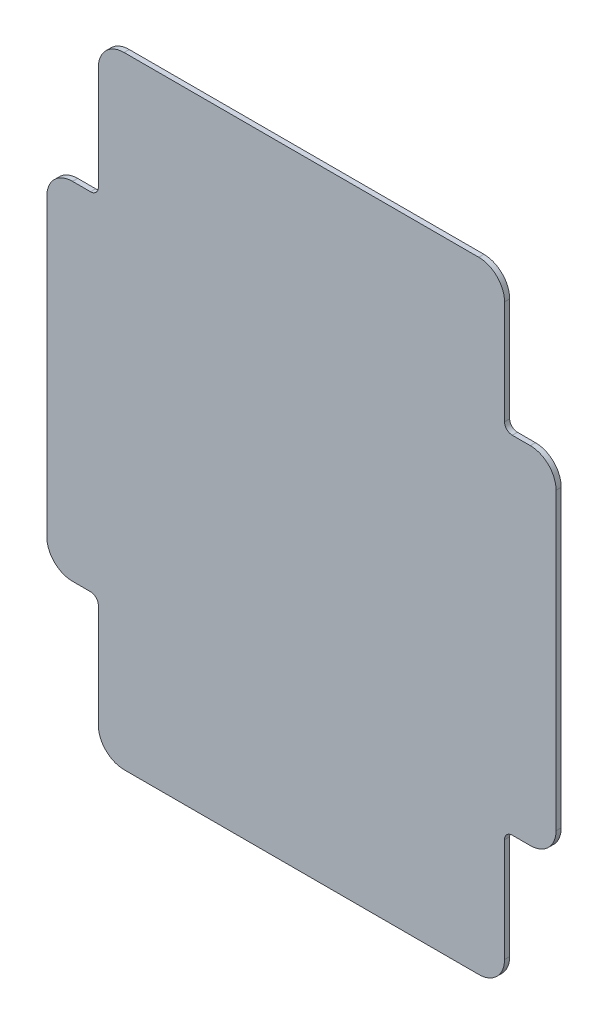
SolidWorks part; units mm, degrees
ref_plane "Ön Düzlem" through (0, 0, 0) normal (0, 0, 1) x (1, 0, 0)
ref_plane "Üst Düzlem" through (0, 0, 0) normal (0, 1, 0) x (1, 0, 0)
ref_plane "Sağ Düzlem" through (0, 0, 0) normal (1, 0, 0) x (0, 0, -1)
sketch "Çizim1" plane through (0, 0, 0) normal (0, 0, 1) x (1, 0, 0)
  line L0 (78.3978, 53) -> (78.3978, 58)
  line L1 (78.3978, 58) -> (-79.2022, 58)
  line L2 (-79.2022, 58) -> (-79.2022, 53)
  line L3 (-79.2022, 53) -> (-79.2022, 4.7)
  line L4 (-79.2022, 4.7) -> (-99.2022, 4.7)
  line L5 (-99.2022, 4.7) -> (-99.2022, -129.7)
  line L6 (-99.2022, -129.7) -> (-79.2022, -129.7)
  line L7 (-79.2022, -129.7) -> (-79.2022, -178)
  line L8 (-79.2022, -178) -> (-79.2022, -183)
  line L9 (-79.2022, -183) -> (78.3978, -183)
  line L10 (78.3978, -183) -> (78.3978, -178)
  line L11 (78.3978, -178) -> (78.3978, -129.7)
  line L12 (78.3978, -129.7) -> (98.3978, -129.7)
  line L13 (98.3978, -129.7) -> (98.3978, 4.7)
  line L14 (98.3978, 4.7) -> (78.3978, 4.7)
  line L15 (78.3978, 4.7) -> (78.3978, 53)
  dimension "D1" = 5
  dimension "D2" = 5
  dimension "D3" = 20
  dimension "D4" = 20
extrude "Yükseklik-Ekstrüzyon1" add sketch "Çizim1" along normal blind 2 contours L3 L4 L5 L6 L7 L8 L9 L10 L11 L12 L13 L14 L15 L0 L1 L2
fillet "Radyus1" radius 10 8 edges at (-79.2022, 58, 1) (-99.2022, 4.7, 1) (-99.2022, -129.7, 1) (-79.2022, -183, 1) (78.3978, -183, 1) (98.3978, -129.7, 1) (98.3978, 4.7, 1) (78.3978, 58, 1)
fillet "Radyus2" radius 3 4 edges at (-79.2022, -129.7, 1) (78.3978, -129.7, 1) (78.3978, 4.7, 1) (-79.2022, 4.7, 1)
sketch "Çizim2" plane through (0, 0, 0) normal (0, 0, -1) x (-1, 0, 0)
  line L0 (69.2022, -183) -> (-68.3978, -183) construction
  line L1 (-59.5978, -145.55) -> (-57.4978, -145.55)
  line L2 (-59.5978, -145.55) -> (-59.5978, -173.55)
  line L3 (-59.5978, -173.55) -> (-57.4978, -173.55)
  line L4 (-57.4978, -145.55) -> (-57.4978, -173.55)
  line L5 (-78.3978, -173) -> (-78.3978, -132.7) construction
  line L6 (0.4022, 58) -> (0.4022, -183) construction
  line L7 (-68.3978, 58) -> (69.2022, 58) construction
  line L8 (-98.3978, -62.5) -> (99.2022, -62.5) construction
  line L9 (-98.3978, -119.7) -> (-98.3978, -5.3) construction
  line L10 (99.2022, -5.3) -> (99.2022, -119.7) construction
  line L11 (58.3022, -145.55) -> (58.3022, -173.55)
  line L12 (60.4022, -173.55) -> (58.3022, -173.55)
  line L13 (60.4022, -145.55) -> (60.4022, -173.55)
  line L14 (60.4022, -145.55) -> (58.3022, -145.55)
  line L15 (60.4022, 20.55) -> (58.3022, 20.55)
  line L16 (60.4022, 20.55) -> (60.4022, 48.55)
  line L17 (60.4022, 48.55) -> (58.3022, 48.55)
  line L18 (58.3022, 20.55) -> (58.3022, 48.55)
  line L19 (-57.4978, 20.55) -> (-57.4978, 48.55)
  line L20 (-59.5978, 48.55) -> (-57.4978, 48.55)
  line L21 (-59.5978, 20.55) -> (-59.5978, 48.55)
  line L22 (-59.5978, 20.55) -> (-57.4978, 20.55)
  dimension "D1" = 2.1
  dimension "D2" = 9.45
  dimension "D3" = 18.8
  dimension "D4" = 28
extrude "Kes-Ekstrüzyon1" [suppressed] cut sketch "Çizim2" against normal blind 10
sketch "Çizim3" plane through (0, 0, 0) normal (0, 0, -1) x (-1, 0, 0)
  line L0 (79.5821, -100.537) -> (63.7567, -100.537)
  line L1 (59.7567, -104.537) -> (59.7567, -105.7328)
  line L2 (55.7567, -109.7328) -> (52.471, -109.7328)
  line L3 (48.471, -105.7328) -> (48.471, -76.5317)
  line L4 (48.471, -65.4259) -> (42.4393, -65.4259)
  line L5 (38.4393, -61.4259) -> (38.4393, -0.4577)
  line L6 (42.4393, 3.5423) -> (50.1138, 3.5423)
  line L7 (54.1138, -0.4577) -> (54.1138, -16.2831)
  line L8 (58.1138, -20.2831) -> (79.5821, -20.2831)
  line L9 (83.5821, -24.2831) -> (83.5821, -61.4259)
  line L10 (0.4022, -183) -> (0.4022, 58) construction
  line L11 (48.471, -65.4259) -> (79.5821, -65.4259)
  line L13 (52.471, -72.5317) -> (79.5821, -72.5317)
  line L15 (69.2022, -183) -> (-68.3978, -183) construction
  line L16 (-68.3978, 58) -> (69.2022, 58) construction
  line L31 (83.5821, -76.5317) -> (83.5821, -96.537)
  line L33 (-82.7776, -76.5317) -> (-82.7776, -96.537)
  line L34 (-51.6665, -72.5317) -> (-78.7776, -72.5317)
  line L35 (-47.6665, -65.4259) -> (-78.7776, -65.4259)
  line L36 (-82.7776, -24.2831) -> (-82.7776, -61.4259)
  line L37 (-57.3094, -20.2831) -> (-78.7776, -20.2831)
  line L38 (-53.3094, -0.4577) -> (-53.3094, -16.2831)
  line L39 (-41.6348, 3.5423) -> (-49.3094, 3.5423)
  line L40 (-37.6348, -61.4259) -> (-37.6348, -0.4577)
  line L41 (-47.6665, -65.4259) -> (-41.6348, -65.4259)
  line L42 (-47.6665, -105.7328) -> (-47.6665, -76.5317)
  line L43 (-54.9522, -109.7328) -> (-51.6665, -109.7328)
  line L44 (-58.9522, -104.537) -> (-58.9522, -105.7328)
  line L45 (-78.7776, -100.537) -> (-62.9522, -100.537)
  arc A0 (79.5821, -65.4259) -> (83.5821, -61.4259) centre (79.5821, -61.4259) ccw
  arc A1 (79.5821, -20.2831) -> (83.5821, -24.2831) centre (79.5821, -24.2831) cw
  arc A2 (54.1138, -16.2831) -> (58.1138, -20.2831) centre (58.1138, -16.2831) ccw
  arc A3 (50.1138, 3.5423) -> (54.1138, -0.4577) centre (50.1138, -0.4577) cw
  arc A4 (38.4393, -0.4577) -> (42.4393, 3.5423) centre (42.4393, -0.4577) cw
  arc A5 (42.4393, -65.4259) -> (38.4393, -61.4259) centre (42.4393, -61.4259) cw
  arc A6 (52.471, -109.7328) -> (48.471, -105.7328) centre (52.471, -105.7328) cw
  arc A7 (48.471, -76.5317) -> (52.471, -72.5317) centre (52.471, -76.5317) cw
  arc A8 (79.5821, -72.5317) -> (83.5821, -76.5317) centre (79.5821, -76.5317) cw
  arc A9 (79.5821, -100.537) -> (83.5821, -96.537) centre (79.5821, -96.537) ccw
  arc A10 (63.7567, -100.537) -> (59.7567, -104.537) centre (63.7567, -104.537) ccw
  arc A11 (59.7567, -105.7328) -> (55.7567, -109.7328) centre (55.7567, -105.7328) cw
  arc A12 (-58.9522, -105.7328) -> (-54.9522, -109.7328) centre (-54.9522, -105.7328) ccw
  arc A13 (-62.9522, -100.537) -> (-58.9522, -104.537) centre (-62.9522, -104.537) cw
  arc A14 (-78.7776, -100.537) -> (-82.7776, -96.537) centre (-78.7776, -96.537) cw
  arc A15 (-78.7776, -72.5317) -> (-82.7776, -76.5317) centre (-78.7776, -76.5317) ccw
  arc A16 (-47.6665, -76.5317) -> (-51.6665, -72.5317) centre (-51.6665, -76.5317) ccw
  arc A17 (-51.6665, -109.7328) -> (-47.6665, -105.7328) centre (-51.6665, -105.7328) ccw
  arc A18 (-41.6348, -65.4259) -> (-37.6348, -61.4259) centre (-41.6348, -61.4259) ccw
  arc A19 (-37.6348, -0.4577) -> (-41.6348, 3.5423) centre (-41.6348, -0.4577) ccw
  arc A20 (-49.3094, 3.5423) -> (-53.3094, -0.4577) centre (-49.3094, -0.4577) ccw
  arc A21 (-53.3094, -16.2831) -> (-57.3094, -20.2831) centre (-57.3094, -16.2831) cw
  arc A22 (-78.7776, -20.2831) -> (-82.7776, -24.2831) centre (-78.7776, -24.2831) ccw
  arc A23 (-78.7776, -65.4259) -> (-82.7776, -61.4259) centre (-78.7776, -61.4259) cw
  point P34 (83.5821, -65.4259)
  point P37 (83.5821, -20.2831)
  point P40 (54.1138, -20.2831)
  point P43 (54.1138, 3.5423)
  point P46 (38.4393, 3.5423)
  point P49 (38.4393, -65.4259)
  point P52 (48.471, -109.7328)
  point P55 (48.471, -72.5317)
  point P58 (83.5821, -72.5317)
  point P61 (83.5821, -100.537)
  point P64 (59.7567, -100.537)
  point P67 (59.7567, -109.7328)
  point P92 (-58.9522, -109.7328)
  point P93 (-58.9522, -100.537)
  point P94 (-82.7776, -100.537)
  point P95 (-82.7776, -72.5317)
  point P96 (-47.6665, -72.5317)
  point P97 (-47.6665, -109.7328)
  point P98 (-37.6348, -65.4259)
  point P99 (-37.6348, 3.5423)
  point P100 (-53.3094, 3.5423)
  point P101 (-53.3094, -20.2831)
  point P102 (-82.7776, -20.2831)
  point P103 (-82.7776, -65.4259)
  dimension "D1" = 4
extrude "Kes-Ekstrüzyon2" [suppressed] cut sketch "Çizim3" against normal blind 10
sketch "Çizim4" plane through (0, 0, 0) normal (0, 0, -1) x (-1, 0, 0)
  line L0 (99.2022, -62.5) -> (49.2022, -62.5) construction
  line L1 (0.4022, 58) -> (0.4022, 77.8983) construction
  line L2 (-98.3978, -62.5) -> (-48.3978, -62.5) construction
  circle A0 centre (49.2022, -175) radius 1.6
  circle A1 centre (56.2022, -138) radius 1.6
  circle A2 centre (1.2022, -76) radius 1.6
  circle A3 centre (1.2022, -178) radius 1.6
  circle A4 centre (92.2022, -99.7) radius 1.6
  circle A5 centre (92.2022, -25.3) radius 1.6
  circle A6 centre (56.2022, 13) radius 1.6
  circle A7 centre (49.2022, 50) radius 1.6
  circle A8 centre (-48.3978, 50) radius 1.6
  circle A9 centre (-55.3978, 13) radius 1.6
  circle A10 centre (-91.3978, -25.3) radius 1.6
  circle A11 centre (-91.3978, -99.7) radius 1.6
  circle A12 centre (-55.3978, -138) radius 1.6
  circle A13 centre (-48.3978, -175) radius 1.6
  dimension "D1" = 3.2
extrude "Kes-Ekstrüzyon3" [suppressed] cut sketch "Çizim4" against normal blind 10
